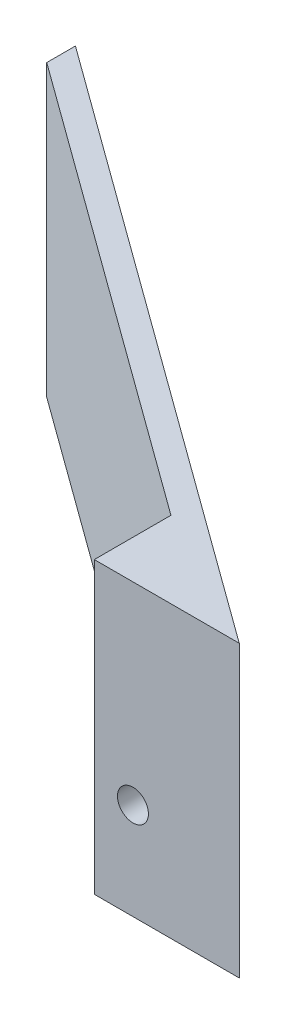
SolidWorks part; units mm, degrees
ref_plane "前视基准面" through (0, 0, 0) normal (0, 0, 1) x (1, 0, 0)
ref_plane "上视基准面" through (0, 0, 0) normal (0, 1, 0) x (1, 0, 0)
ref_plane "右视基准面" through (0, 0, 0) normal (1, 0, 0) x (0, 0, -1)
sketch "草图1" plane through (0, 0, 0) normal (0, 1, 0) x (1, 0, 0)
  line L0 (0, 0) -> (-62, 45.0456)
  line L1 (-62, 45.0456) -> (-62, 42.0791)
  line L2 (-62, 42.0791) -> (-15, 7.9316)
  line L3 (-15, 7.9316) -> (-15, 0)
  line L4 (-15, 0) -> (0, 0)
  line L5 (0, 0) -> (0, 51.8386) construction
  point P7 (0, 0)
  dimension "D1" = 62
  dimension "D2" = 2.4
  dimension "D3" = 15
  dimension "D4" = 54
  dimension "D5" = 45.0456
extrude "凸台-拉伸1" add sketch "草图1" along normal blind 30
sketch "草图2" plane through (0, 0, 0) normal (0, 0, 1) x (1, 0, 0)
  line L0 (-15, 0) -> (0, 0) construction
  line L1 (-15, 30) -> (-15, 0) construction
  circle A0 centre (-11, 10) radius 1.6
  dimension "D1" = 3.2
  dimension "D2" = 10
  dimension "D3" = 4
extrude "切除-拉伸1" cut sketch "草图2" against normal through all
ref_plane "基准面1" through (0, 0, -3) normal (0, 0, 1) x (1, 0, 0)
sketch "草图3" plane through (0, 0, -3) normal (0, 0, 1) x (1, 0, 0)
  circle A0 centre (-11, 10) radius 3
  dimension "D1" = 6
extrude "切除-拉伸2" cut sketch "草图3" against normal up to next
